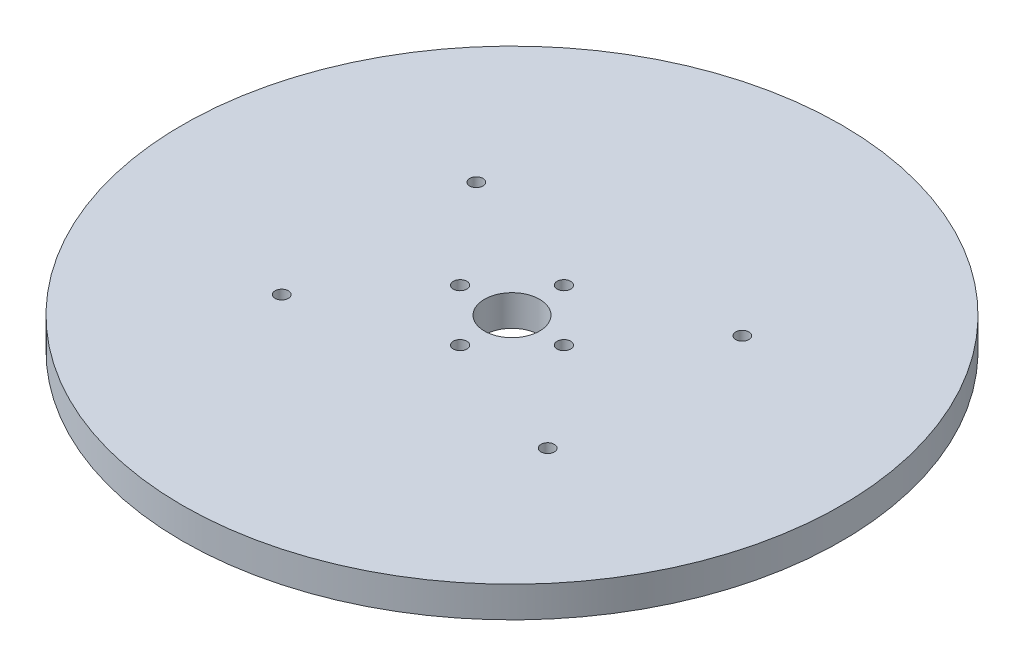
SolidWorks part; units mm, degrees
ref_plane "Front Plane" through (0, 0, 0) normal (0, 0, 1) x (1, 0, 0)
ref_plane "Top Plane" through (0, 0, 0) normal (0, 1, 0) x (1, 0, 0)
ref_plane "Right Plane" through (0, 0, 0) normal (1, 0, 0) x (0, 0, -1)
sketch "Sketch1" plane through (0, 0, 0) normal (0, 1, 0) x (1, 0, 0)
  circle A0 centre (0, 0) radius 50.8
  dimension "D1" = 101.6
extrude "Boss-Extrude1" add sketch "Sketch1" along normal blind 4.7625
sketch "Sketch2" plane through (0, 4.7625, 0) normal (0, 1, 0) x (-1, 0, 0)
  line L0 (8, 0) -> (-8, 0) construction
  line L1 (0, 8) -> (0, -8) construction
  circle A0 centre (0, 8) radius 1.05
  circle A1 centre (-8, 0) radius 1.05
  circle A2 centre (0, -8) radius 1.05
  circle A3 centre (8, 0) radius 1.05
  dimension "D1" = 2.1
  dimension "D2" = 16
extrude "Cut-Extrude1" cut sketch "Sketch2" against normal through all
sketch "Sketch3" plane through (0, 4.7625, 0) normal (0, 1, 0) x (-1, 0, 0)
  circle A0 centre (0, 0) radius 4.25
  dimension "D1" = 8.5
extrude "Cut-Extrude2" cut sketch "Sketch3" against normal through all
sketch "Sketch4" plane through (0, 4.7625, 0) normal (0, 1, 0) x (-1, 0, 0)
  line L1 (-20.5, -15) -> (20.5, -15) construction
  line L2 (-20.5, -15) -> (-20.5, 15) construction
  line L3 (-20.5, 15) -> (20.5, 15) construction
  line L4 (20.5, -15) -> (20.5, 15) construction
  line L5 (-20.5, -15) -> (20.5, 15) construction
  line L6 (-20.5, 15) -> (20.5, -15) construction
  circle A0 centre (-20.5, 15) radius 1.025
  circle A1 centre (20.5, 15) radius 1.025
  circle A2 centre (20.5, -15) radius 1.025
  circle A3 centre (-20.5, -15) radius 1.025
  point P0 (0, 0)
  dimension "D3" = 2.05
  dimension "D1" = 41
  dimension "D2" = 30
extrude "Cut-Extrude3" cut sketch "Sketch4" against normal through all
sketch "Sketch6" plane through (0, 0, 0) normal (0, -1, 0) x (1, 0, 0)
  line L1 (-20.5, -15) -> (20.5, -15) construction
  line L2 (-20.5, -15) -> (-20.5, 15) construction
  line L3 (-20.5, 15) -> (20.5, 15) construction
  line L4 (20.5, -15) -> (20.5, 15) construction
  line L5 (-20.5, -15) -> (20.5, 15) construction
  line L6 (-20.5, 15) -> (20.5, -15) construction
  line L7 (-17.6421, 15) -> (-19.0711, 17.475)
  line L8 (-19.0711, 17.475) -> (-21.9289, 17.475)
  line L9 (-21.9289, 17.475) -> (-23.3579, 15)
  line L10 (-23.3579, 15) -> (-21.9289, 12.525)
  line L11 (-21.9289, 12.525) -> (-19.0711, 12.525)
  line L12 (-19.0711, 12.525) -> (-17.6421, 15)
  line L13 (21.9289, 17.475) -> (19.0711, 17.475)
  line L14 (19.0711, 17.475) -> (17.6421, 15)
  line L15 (17.6421, 15) -> (19.0711, 12.525)
  line L16 (19.0711, 12.525) -> (21.9289, 12.525)
  line L17 (21.9289, 12.525) -> (23.3579, 15)
  line L18 (23.3579, 15) -> (21.9289, 17.475)
  line L19 (21.9289, -12.525) -> (19.0711, -12.525)
  line L20 (19.0711, -12.525) -> (17.6421, -15)
  line L21 (17.6421, -15) -> (19.0711, -17.475)
  line L22 (19.0711, -17.475) -> (21.9289, -17.475)
  line L23 (21.9289, -17.475) -> (23.3579, -15)
  line L24 (23.3579, -15) -> (21.9289, -12.525)
  line L25 (-21.9289, -12.525) -> (-23.3579, -15)
  line L26 (-23.3579, -15) -> (-21.9289, -17.475)
  line L27 (-21.9289, -17.475) -> (-19.0711, -17.475)
  line L28 (-19.0711, -17.475) -> (-17.6421, -15)
  line L29 (-17.6421, -15) -> (-19.0711, -12.525)
  line L30 (-19.0711, -12.525) -> (-21.9289, -12.525)
  circle A0 centre (0, 0) radius 15
  circle A1 centre (-20.5, 15) radius 2.475 construction
  circle A2 centre (20.5, 15) radius 2.475 construction
  circle A3 centre (20.5, -15) radius 2.475 construction
  circle A4 centre (-20.5, -15) radius 2.475 construction
  arc A5 (-13.1298, 16.3893) -> (-19.594, 7.5549) centre (-20.5, 15) ccw
  arc A6 (19.594, 7.5549) -> (13.1298, 16.3893) centre (20.5, 15) ccw
  arc A7 (-19.594, 7.5549) -> (-19.594, -7.5549) centre (0, 0) ccw
  arc A8 (-19.594, -7.5549) -> (-13.1298, -16.3893) centre (-20.5, -15) ccw
  arc A9 (13.1298, -16.3893) -> (19.594, -7.5549) centre (20.5, -15) ccw
  arc A10 (13.1298, 16.3893) -> (-13.1298, 16.3893) centre (0, 0) ccw
  arc A11 (19.594, -7.5549) -> (19.594, 7.5549) centre (0, 0) ccw
  arc A12 (-13.1298, -16.3893) -> (13.1298, -16.3893) centre (0, 0) ccw
  dimension "D2" = 30
  dimension "D3" = 15
  dimension "D4" = 6
  dimension "D1" = 4.95
extrude "Boss-Extrude2" add sketch "Sketch6" along normal blind 1.5875 separate body
sketch "Sketch7" plane through (0, -1.5875, 0) normal (0, -1, 0) x (1, 0, 0)
  line L0 (-19.0711, 12.525) -> (-17.6421, 15) construction
  line L1 (-17.6421, 15) -> (-19.0711, 17.475) construction
  line L2 (-19.0711, 17.475) -> (-21.9289, 17.475) construction
  line L3 (-21.9289, 17.475) -> (-23.3579, 15) construction
  line L4 (-23.3579, 15) -> (-21.9289, 12.525) construction
  line L5 (-21.9289, 12.525) -> (-19.0711, 12.525) construction
  line L6 (21.9289, 17.475) -> (19.0711, 17.475) construction
  line L7 (23.3579, 15) -> (21.9289, 17.475) construction
  line L8 (21.9289, 12.525) -> (23.3579, 15) construction
  line L9 (19.0711, 12.525) -> (21.9289, 12.525) construction
  line L10 (17.6421, 15) -> (19.0711, 12.525) construction
  line L11 (19.0711, 17.475) -> (17.6421, 15) construction
  line L12 (21.9289, -12.525) -> (19.0711, -12.525) construction
  line L13 (23.3579, -15) -> (21.9289, -12.525) construction
  line L14 (21.9289, -17.475) -> (23.3579, -15) construction
  line L15 (19.0711, -17.475) -> (21.9289, -17.475) construction
  line L16 (17.6421, -15) -> (19.0711, -17.475) construction
  line L17 (19.0711, -12.525) -> (17.6421, -15) construction
  line L18 (-19.0711, -12.525) -> (-21.9289, -12.525) construction
  line L19 (-17.6421, -15) -> (-19.0711, -12.525) construction
  line L20 (-19.0711, -17.475) -> (-17.6421, -15) construction
  line L21 (-21.9289, -17.475) -> (-19.0711, -17.475) construction
  line L22 (-23.3579, -15) -> (-21.9289, -17.475) construction
  line L23 (-21.9289, -12.525) -> (-23.3579, -15) construction
  line L24 (-19.0711, 12.525) -> (-17.6421, 15)
  line L25 (-17.6421, 15) -> (-19.0711, 17.475)
  line L26 (-19.0711, 17.475) -> (-21.9289, 17.475)
  line L27 (-21.9289, 17.475) -> (-23.3579, 15)
  line L28 (-23.3579, 15) -> (-21.9289, 12.525)
  line L29 (-21.9289, 12.525) -> (-19.0711, 12.525)
  line L30 (21.9289, 17.475) -> (19.0711, 17.475)
  line L31 (23.3579, 15) -> (21.9289, 17.475)
  line L32 (21.9289, 12.525) -> (23.3579, 15)
  line L33 (19.0711, 12.525) -> (21.9289, 12.525)
  line L34 (17.6421, 15) -> (19.0711, 12.525)
  line L35 (19.0711, 17.475) -> (17.6421, 15)
  line L36 (21.9289, -12.525) -> (19.0711, -12.525)
  line L37 (23.3579, -15) -> (21.9289, -12.525)
  line L38 (21.9289, -17.475) -> (23.3579, -15)
  line L39 (19.0711, -17.475) -> (21.9289, -17.475)
  line L40 (17.6421, -15) -> (19.0711, -17.475)
  line L41 (19.0711, -12.525) -> (17.6421, -15)
  line L42 (-19.0711, -12.525) -> (-21.9289, -12.525)
  line L43 (-17.6421, -15) -> (-19.0711, -12.525)
  line L44 (-19.0711, -17.475) -> (-17.6421, -15)
  line L45 (-21.9289, -17.475) -> (-19.0711, -17.475)
  line L46 (-23.3579, -15) -> (-21.9289, -17.475)
  line L47 (-21.9289, -12.525) -> (-23.3579, -15)
  circle A0 centre (0, 0) radius 15 construction
  circle A1 centre (0, 0) radius 15
  arc A8 (13.1298, 16.3893) -> (-13.1298, 16.3893) centre (0, 0) ccw
  arc A9 (-13.1298, 16.3893) -> (-19.594, 7.5549) centre (-20.5, 15) ccw
  arc A10 (-19.594, 7.5549) -> (-19.594, -7.5549) centre (0, 0) ccw
  arc A11 (-19.594, -7.5549) -> (-13.1298, -16.3893) centre (-20.5, -15) ccw
  arc A12 (-13.1298, -16.3893) -> (13.1298, -16.3893) centre (0, 0) ccw
  arc A13 (13.1298, -16.3893) -> (19.594, -7.5549) centre (20.5, -15) ccw
  arc A14 (19.594, -7.5549) -> (19.594, 7.5549) centre (0, 0) ccw
  arc A15 (19.594, 7.5549) -> (13.1298, 16.3893) centre (20.5, 15) ccw
  arc A16 (13.1298, 16.3893) -> (-13.1298, 16.3893) centre (0, 0) ccw
  arc A17 (-13.1298, 16.3893) -> (-19.594, 7.5549) centre (-20.5, 15) ccw
  arc A18 (-19.594, 7.5549) -> (-19.594, -7.5549) centre (0, 0) ccw
  arc A19 (-19.594, -7.5549) -> (-13.1298, -16.3893) centre (-20.5, -15) ccw
  arc A20 (-13.1298, -16.3893) -> (13.1298, -16.3893) centre (0, 0) ccw
  arc A21 (13.1298, -16.3893) -> (19.594, -7.5549) centre (20.5, -15) ccw
  arc A22 (19.594, -7.5549) -> (19.594, 7.5549) centre (0, 0) ccw
  arc A23 (19.594, 7.5549) -> (13.1298, 16.3893) centre (20.5, 15) ccw
  dimension "D1" = 0
sketch "Sketch8" plane through (0, 4.7625, 0) normal (0, 1, 0) x (1, 0, 0)
  circle A0 centre (-20.5, 15) radius 1.025 construction
  circle A1 centre (0, 0) radius 50.8
  circle A2 centre (0, 0) radius 50.8
  circle A3 centre (20.5, 15) radius 1.025 construction
  circle A4 centre (20.5, -15) radius 1.025 construction
  circle A5 centre (-20.5, -15) radius 1.025 construction
  circle A6 centre (0, 0) radius 4.25 construction
  circle A7 centre (-8, 0) radius 1.05 construction
  circle A8 centre (0, 8) radius 1.05 construction
  circle A9 centre (8, 0) radius 1.05 construction
  circle A10 centre (0, -8) radius 1.05 construction
  circle A11 centre (-20.5, 15) radius 1.025
  circle A12 centre (20.5, 15) radius 1.025
  circle A13 centre (20.5, -15) radius 1.025
  circle A14 centre (-20.5, -15) radius 1.025
  circle A15 centre (0, 0) radius 4.25
  circle A16 centre (-8, 0) radius 1.05
  circle A17 centre (0, 8) radius 1.05
  circle A18 centre (8, 0) radius 1.05
  circle A19 centre (0, -8) radius 1.05
  dimension "D1" = 0
